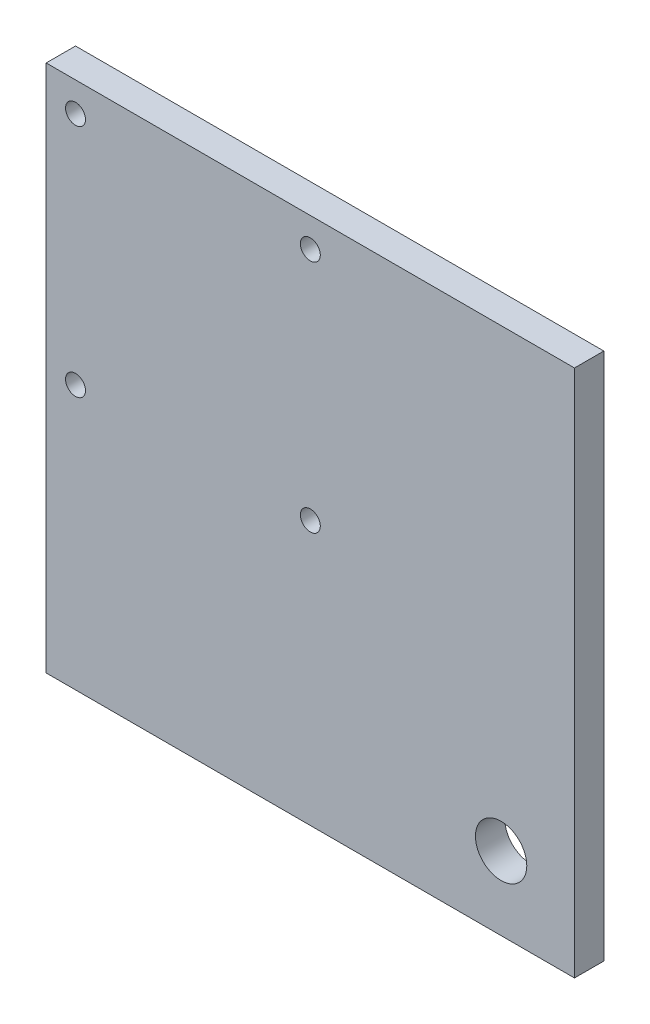
SolidWorks part; units mm, degrees
ref_plane "前视基准面" through (0, 0, 0) normal (0, 0, 1) x (1, 0, 0)
ref_plane "上视基准面" through (0, 0, 0) normal (0, 1, 0) x (1, 0, 0)
ref_plane "右视基准面" through (0, 0, 0) normal (1, 0, 0) x (0, 0, -1)
sketch "草图1" plane through (0, 0, 0) normal (0, 0, 1) x (-1, 0, 0)
  line L8 (-25, 250) -> (-25, 70)
  line L9 (-25, 70) -> (155, 70)
  line L10 (155, 70) -> (155, 250)
  line L11 (155, 250) -> (-25, 250)
  circle A2 centre (145, 160) radius 3.4
  circle A4 centre (65, 160) radius 3.4
  circle A6 centre (0, 225) radius 8.75
  circle A8 centre (145, 80) radius 3.4
  circle A10 centre (65, 80) radius 3.4
  dimension "D1" = 180
extrude "凸台-拉伸1" add sketch "草图1" along normal blind 10
